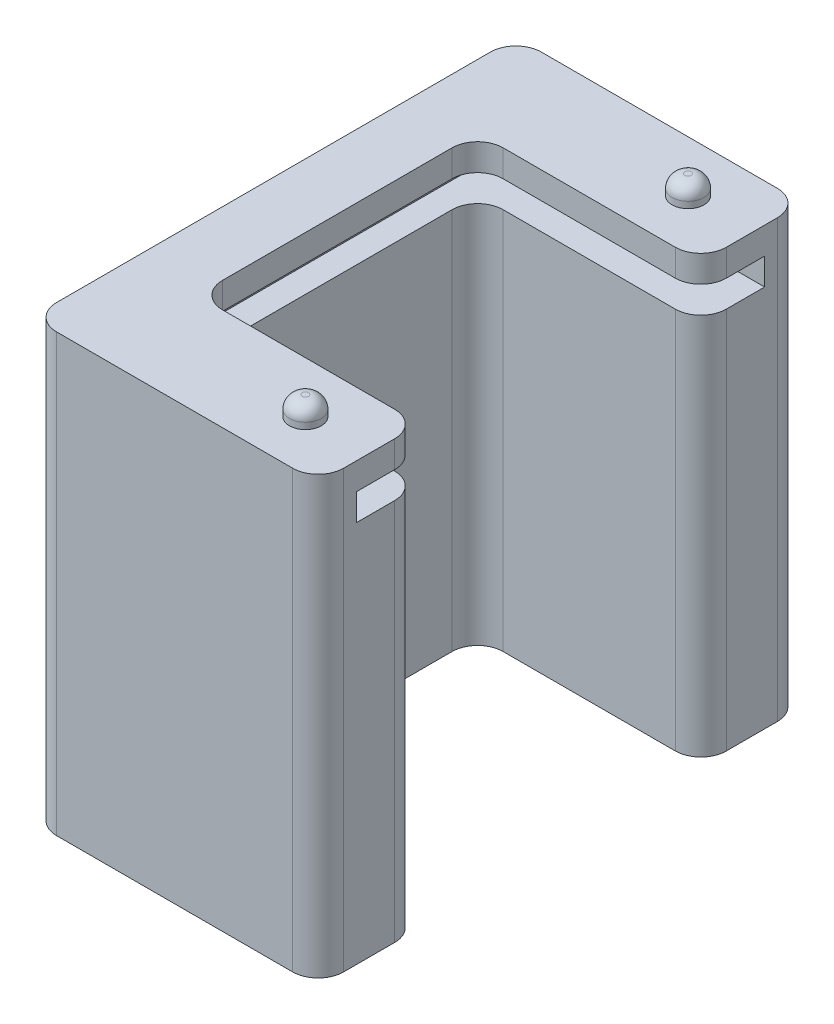
SolidWorks part; units mm, degrees
material "Aleación 1060"
ref_plane "Alzado" through (0, 0, 0) normal (0, 0, 1) x (1, 0, 0)
ref_plane "Planta" through (0, 0, 0) normal (0, 1, 0) x (1, 0, 0)
ref_plane "Vista lateral" through (0, 0, 0) normal (1, 0, 0) x (0, 0, -1)
sketch "Croquis1" plane through (0, 0, 0) normal (0, 1, 0) x (1, 0, 0)
  line L0 (0, 0) -> (22.5, 0)
  line L1 (22.5, 0) -> (22.5, 8)
  line L2 (22.5, 8) -> (5, 8)
  line L3 (5, 8) -> (5, 30)
  line L4 (5, 30) -> (22.5, 30)
  line L5 (22.5, 30) -> (22.5, 38)
  line L6 (22.5, 38) -> (0, 38)
  line L7 (0, 38) -> (0, 0)
  dimension "D1" = 38
  dimension "D2" = 8
  dimension "D3" = 8
  dimension "D4" = 5
  dimension "D5" = 22.5
  dimension "D6" = 22.5
extrude "Saliente-Extruir1" add sketch "Croquis1" along normal blind 30
fillet "Redondeo1" radius 2 8 edges at (5, 15, -30) (5, 15, -8) (22.5, 15, -8) (22.5, 15, 0) (22.5, 15, -30) (22.5, 15, -38) (0, 15, 0) (0, 15, -38)
sketch "Croquis2" plane through (0, 0, 0) normal (-1, 0, 0) x (0, 0, 1)
  line L0 (-36, 30) -> (-36, 0) construction
  line L3 (-36, 30) -> (-2, 30) construction
  circle A0 centre (-19, 15) radius 4
  dimension "D1" = 8
  dimension "D2" = 17
  dimension "D3" = 15
extrude "Saliente-Extruir2" add sketch "Croquis2" along normal blind 12.2
sketch "Croquis3" plane through (0, 30, 0) normal (0, 1, 0) x (1, 0, 0)
  line L0 (20.5, 38) -> (2, 38)
  line L1 (0, 36) -> (0, 2)
  line L2 (2, 0) -> (20.5, 0)
  line L3 (22.5, 2) -> (22.5, 3)
  line L4 (22.5, 2) -> (22.5, 6) construction
  line L5 (22.5, 3) -> (3, 3)
  line L6 (3, 3) -> (3, 35)
  line L7 (3, 35) -> (22.5, 35)
  line L8 (22.5, 32) -> (22.5, 36) construction
  line L9 (22.5, 35) -> (22.5, 36)
  arc A0 (22.5, 36) -> (20.5, 38) centre (20.5, 36) ccw
  arc A1 (2, 38) -> (0, 36) centre (2, 36) ccw
  arc A2 (0, 2) -> (2, 0) centre (2, 2) ccw
  arc A3 (20.5, 0) -> (22.5, 2) centre (20.5, 2) ccw
  dimension "D1" = 3
  dimension "D2" = 3
  dimension "D3" = 3
extrude "Saliente-Extruir3" add sketch "Croquis3" along normal blind 2.1
sketch "Croquis4" plane through (0, 32.1, 0) normal (0, 1, 0) x (1, 0, 0)
  line L0 (20.5, 38) -> (2, 38) construction
  line L1 (7, 30) -> (20.5, 30) construction
  line L2 (22.5, 32) -> (22.5, 36)
  line L3 (20.5, 38) -> (2, 38)
  line L4 (0, 36) -> (0, 2)
  line L5 (2, 0) -> (20.5, 0)
  line L6 (22.5, 2) -> (22.5, 6)
  line L7 (20.5, 8) -> (7, 8)
  line L8 (20.5, 30) -> (7, 30)
  line L9 (5, 10) -> (5, 28)
  arc A0 (20.5, 38) -> (22.5, 36) centre (20.5, 36) cw
  arc A1 (22.5, 36) -> (20.5, 38) centre (20.5, 36) ccw construction
  arc A2 (22.5, 32) -> (20.5, 30) centre (20.5, 32) cw
  arc A3 (20.5, 8) -> (22.5, 6) centre (20.5, 6) cw
  arc A4 (22.5, 2) -> (20.5, 0) centre (20.5, 2) cw
  arc A5 (0, 2) -> (2, 0) centre (2, 2) ccw
  arc A6 (2, 38) -> (0, 36) centre (2, 36) ccw
  arc A7 (7, 8) -> (5, 10) centre (7, 10) cw
  arc A8 (7, 30) -> (5, 28) centre (7, 28) ccw
  arc A9 (7, 30) -> (5, 28) centre (7, 28) ccw construction
extrude "Saliente-Extruir4" add sketch "Croquis4" along normal blind 2.1
sketch "Croquis5" plane through (0, 34.2, 0) normal (0, 1, 0) x (1, 0, 0)
  line L0 (22.5, 32) -> (22.5, 36) construction
  line L1 (22.5, 2) -> (22.5, 6) construction
  circle A0 centre (17.5, 34) radius 1.25
  circle A1 centre (17.5, 4) radius 1.25
  dimension "D3" = 2.5
  dimension "D4" = 2.5
  dimension "D1" = 5
  dimension "D2" = 5
extrude "Saliente-Extruir5" add sketch "Croquis5" along normal blind 1.5
fillet "Redondeo2" radius 1 2 edges at (17.5, 35.7, -2.75) (17.5, 35.7, -32.75)
sketch "Croquis6" plane through (0, 0, 0) normal (0, -1, 0) x (1, 0, 0)
  line L0 (22.5, -2) -> (22.5, -6) construction
  line L1 (22.5, -32) -> (22.5, -36) construction
  circle A0 centre (17.5, -4) radius 1.25
  circle A1 centre (17.5, -34) radius 1.25
  dimension "D3" = 2.5
  dimension "D4" = 2.5
  dimension "D1" = 5
  dimension "D2" = 5
extrude "Saliente-Extruir6" add sketch "Croquis6" along normal blind 1.5
fillet "Redondeo3" radius 1 2 edges at (17.5, -1.5, -35.25) (17.5, -1.5, -5.25)
sketch "Croquis7" plane through (-12.2, 0, 0) normal (-1, 0, 0) x (0, 0, 1)
  circle A0 centre (-19, 15) radius 2.5
  dimension "D1" = 5
extrude "Cortar-Extruir1" cut sketch "Croquis7" against normal blind 10
